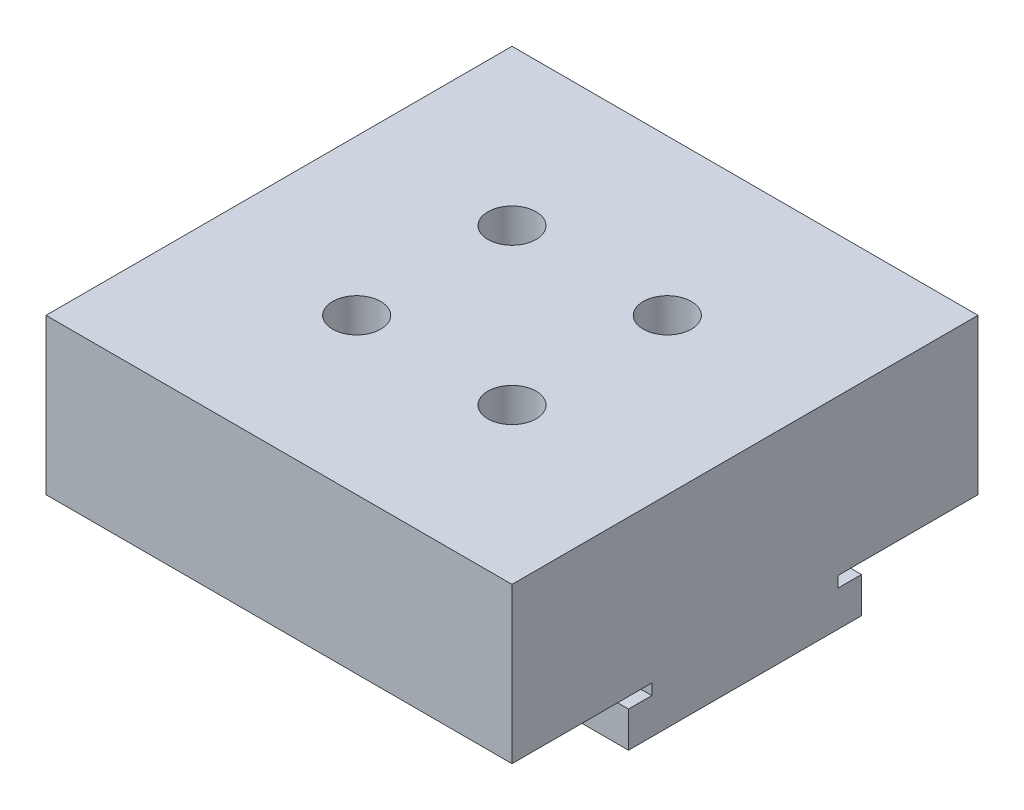
SolidWorks part; units mm, degrees
ref_plane "前视基准面" through (0, 0, 0) normal (0, 0, 1) x (1, 0, 0)
ref_plane "上视基准面" through (0, 0, 0) normal (0, 1, 0) x (1, 0, 0)
ref_plane "右视基准面" through (0, 0, 0) normal (1, 0, 0) x (0, 0, -1)
sketch "草图1" plane through (0, 0, 0) normal (0, 1, 0) x (1, 0, 0)
  line L1 (-5, -5) -> (5, -5) construction
  line L2 (-5, -5) -> (-5, 5) construction
  line L3 (-5, 5) -> (5, 5) construction
  line L4 (5, -5) -> (5, 5) construction
  line L5 (-5, -5) -> (5, 5) construction
  line L6 (-5, 5) -> (5, -5) construction
  line L7 (-15, -15) -> (15, -15)
  line L8 (-15, -15) -> (-15, 15)
  line L9 (-15, 15) -> (15, 15)
  line L10 (15, -15) -> (15, 15)
  line L11 (-15, -15) -> (15, 15) construction
  line L12 (-15, 15) -> (15, -15) construction
  circle A0 centre (-5, 5) radius 1.55
  circle A1 centre (5, 5) radius 1.55
  circle A2 centre (5, -5) radius 1.55
  circle A3 centre (-5, -5) radius 1.55
  point P0 (0, 0)
  point P10 (0, 0)
  dimension "D3" = 3.1
  dimension "D1" = 10
  dimension "D2" = 10
  dimension "D4" = 30
  dimension "D5" = 30
extrude "凸台-拉伸1" add sketch "草图1" along normal blind 10
sketch "草图2" plane through (0, 0, 0) normal (0, -1, 0) x (1, 0, 0)
  circle A0 centre (-5, 5) radius 3.5
  circle A1 centre (5, 5) radius 3.5
  circle A2 centre (5, -5) radius 3.5
  circle A3 centre (-5, -5) radius 3.5
  dimension "D1" = 7
extrude "切除-拉伸1" cut sketch "草图2" against normal blind 3
sketch "草图3" plane through (0, 0, 0) normal (0, -1, 0) x (1, 0, 0)
  line L0 (-15, -15) -> (-15, 15) construction
  line L9 (-15, 7.5) -> (-9, 7.5)
  line L10 (-15, 7.5) -> (-15, -7.5)
  line L11 (-15, -7.5) -> (-9, -7.5)
  line L12 (-9, 7.5) -> (-9, -7.5)
  line L13 (15, 15) -> (15, -15) construction
  line L14 (15, 7.5) -> (9, 7.5)
  line L15 (15, 7.5) -> (15, -7.5)
  line L16 (15, -7.5) -> (9, -7.5)
  line L17 (9, 7.5) -> (9, -7.5)
  line L18 (0, 0) -> (-13.7355, 0) construction
  point P14 (-9, 0)
  dimension "D1" = 15
  dimension "D2" = 6
  dimension "D3" = 6
extrude "凸台-拉伸3" add sketch "草图3" along normal blind 3
sketch "草图5" plane through (-15, 0, 0) normal (-1, 0, 0) x (0, 0, 1)
  line L1 (-7.5, 0) -> (-6, 0)
  line L2 (-7.5, 0) -> (-7.5, -0.7)
  line L3 (-7.5, -0.7) -> (-6, -0.7)
  line L4 (-6, 0) -> (-6, -0.7)
  line L5 (7.5, 0) -> (6, 0)
  line L6 (7.5, 0) -> (7.5, -0.7)
  line L7 (7.5, -0.7) -> (6, -0.7)
  line L8 (6, 0) -> (6, -0.7)
  dimension "D1" = 0.7
  dimension "D2" = 1.5
  dimension "D3" = 1.5
  dimension "D5" = 0.7
extrude "切除-拉伸3" cut sketch "草图5" against normal through all
sketch "草图6" plane through (0, 0, 0) normal (0, -1, 0) x (1, 0, 0)
  circle A0 centre (0, 0) radius 3
  dimension "D1" = 6
extrude "凸台-拉伸4" add sketch "草图6" along normal blind 6
